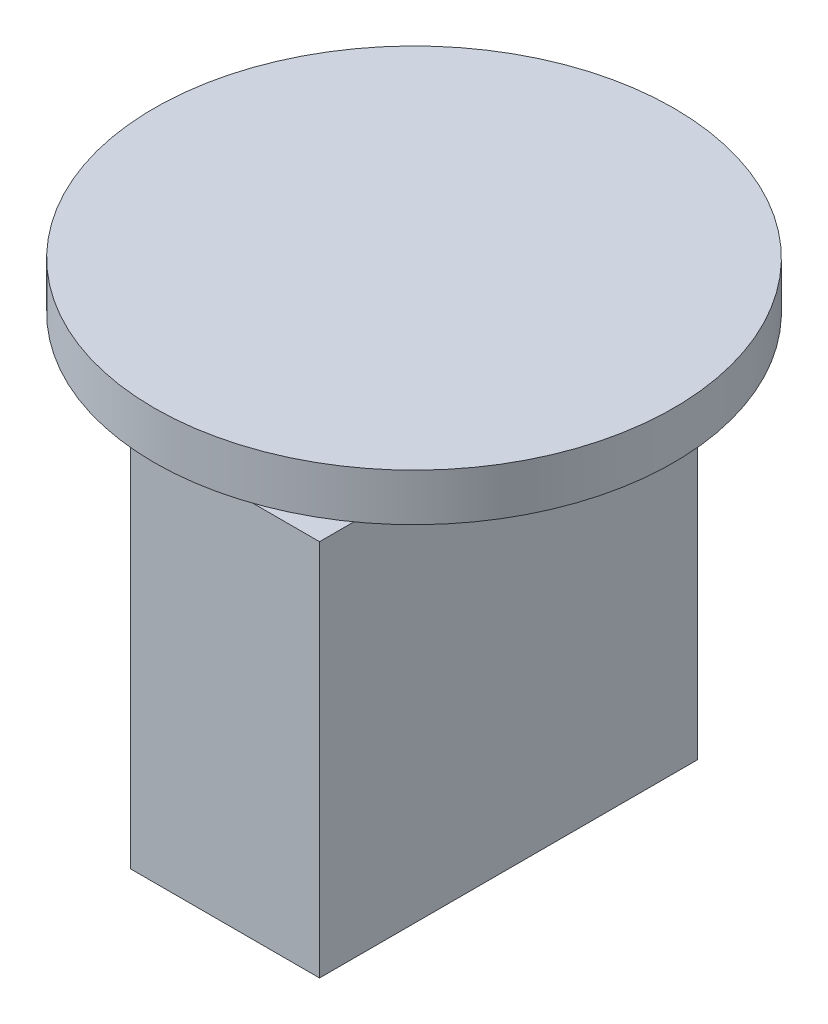
SolidWorks part; units mm, degrees
ref_plane "Front Plane" through (0, 0, 0) normal (0, 0, 1) x (1, 0, 0)
ref_plane "Top Plane" through (0, 0, 0) normal (0, 1, 0) x (1, 0, 0)
ref_plane "Right Plane" through (0, 0, 0) normal (1, 0, 0) x (0, 0, -1)
sketch "Sketch1" plane through (0, 0, 0) normal (0, 1, 0) x (1, 0, 0)
  line L1 (0, 0) -> (-25.4, 0)
  line L2 (0, 0) -> (0, 50.8)
  line L3 (0, 50.8) -> (-25.4, 50.8)
  line L4 (-25.4, 0) -> (-25.4, 50.8)
  dimension "D1" = 25.4
  dimension "D2" = 50.8
extrude "Boss-Extrude1" add sketch "Sketch1" along normal blind 50.8
sketch "Sketch2" plane through (0, 50.8, 0) normal (0, 1, 0) x (1, 0, 0)
  line L0 (0, 50.8) -> (-25.4, 0) construction
  circle A0 centre (-12.7, 25.4) radius 2.54
  dimension "D1" = 5.08
extrude "Boss-Extrude2" add sketch "Sketch2" along normal blind 7.62
sketch "Sketch3" plane through (0, 58.42, 0) normal (0, 1, 0) x (1, 0, 0)
  circle A1 centre (-12.7, 25.4) radius 34.925
  circle A2 centre (-12.7, 25.4) radius 2.54
  circle A3 centre (-12.7, 25.4) radius 2.54 construction
  dimension "D2" = 69.85
  dimension "D1" = 0
extrude "Boss-Extrude3" add sketch "Sketch3" along normal blind 6.35
